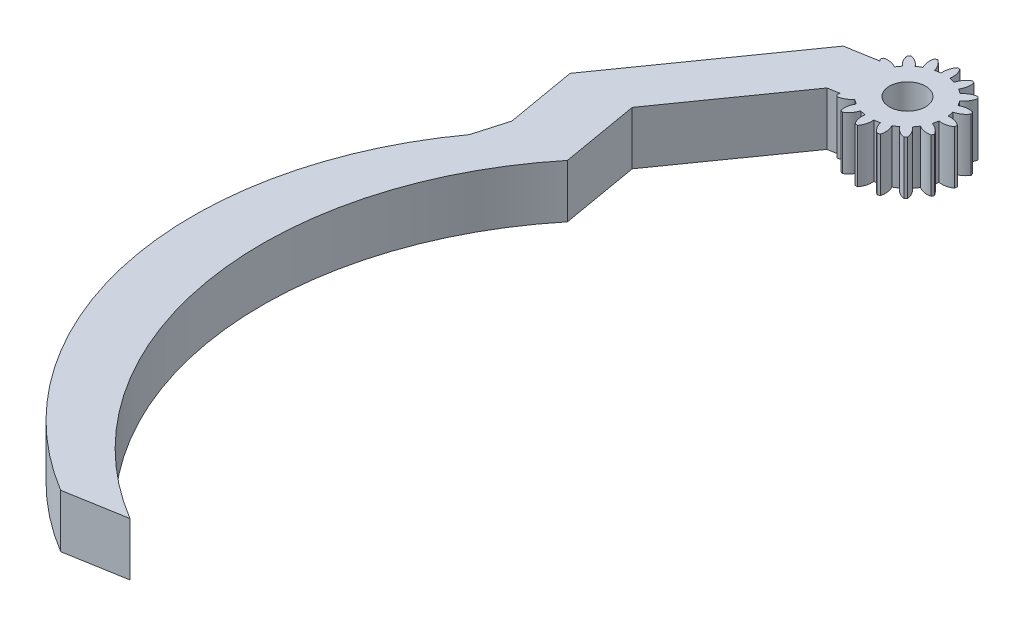
SolidWorks part; units mm, degrees
ref_plane "Front Plane" through (0, 0, 0) normal (0, 0, 1) x (1, 0, 0)
ref_plane "Top Plane" through (0, 0, 0) normal (0, 1, 0) x (1, 0, 0)
ref_plane "Right Plane" through (0, 0, 0) normal (1, 0, 0) x (0, 0, -1)
sketch "Sketch1" plane through (0, 0, 0) normal (0, 1, 0) x (1, 0, 0)
  line L0 (3.0203, 31.1561) -> (1.3998, 30.8763)
  line L1 (1.3998, 30.8763) -> (-10.1283, 14.5359)
  line L2 (-10.1283, 14.5359) -> (-8.192, 3.3226)
  line L3 (4.8849, -72.4068) -> (-3.5689, -73.8666)
  line L4 (-18.4085, -0.4977) -> (-17.0513, 4.211)
  line L5 (-17.0513, 4.211) -> (-18.7961, 14.3151)
  line L6 (-18.7961, 14.3151) -> (-2.6227, 37.2399)
  line L7 (-2.6227, 37.2399) -> (1.8368, 38.01)
  arc A0 (-8.192, 3.3226) -> (4.8849, -72.4068) centre (31.0906, -28.8879) ccw
  arc A1 (-18.4085, -0.4977) -> (-3.5689, -73.8666) centre (22.6783, -30.3727) ccw
  arc A2 (1.6267, 38.3141) -> (1.8368, 38.01) centre (3.8161, 39.6017) ccw
  arc A3 (1.7775, 38.6536) -> (1.6267, 38.3141) centre (8.2284, 35.5846) ccw
  arc A4 (3.6347, 38.3205) -> (1.7775, 38.6536) centre (2.2897, 36.1658) ccw
  arc A5 (4.1104, 38.9948) -> (3.6347, 38.3205) centre (8.2284, 35.5846) ccw
  arc A6 (3.1738, 40.6327) -> (4.1104, 38.9948) centre (5.6893, 40.9845) ccw
  arc A7 (3.443, 40.8886) -> (3.1738, 40.6327) centre (8.2284, 35.5846) ccw
  arc A8 (5.0314, 39.8701) -> (3.443, 40.8886) centre (2.9642, 38.3942) ccw
  arc A9 (5.7289, 40.3111) -> (5.0314, 39.8701) centre (8.2284, 35.5846) ccw
  arc A10 (5.4904, 42.1828) -> (5.7289, 40.3111) centre (7.949, 41.5451) ccw
  arc A11 (5.837, 42.3162) -> (5.4904, 42.1828) centre (8.2284, 35.5846) ccw
  arc A12 (6.9147, 40.7674) -> (5.837, 42.3162) centre (4.4401, 40.1948) ccw
  arc A13 (7.7279, 40.9078) -> (6.9147, 40.7674) centre (8.2284, 35.5846) ccw
  arc A14 (8.2238, 42.7283) -> (7.7279, 40.9078) centre (10.2513, 41.1983) ccw
  arc A15 (8.5951, 42.7189) -> (8.2238, 42.7283) centre (8.2284, 35.5846) ccw
  arc A16 (8.9981, 40.8756) -> (8.5951, 42.7189) centre (6.4927, 41.2936) ccw
  arc A17 (9.8031, 40.6941) -> (8.9981, 40.8756) centre (8.2284, 35.5846) ccw
  arc A18 (10.958, 42.1863) -> (9.8031, 40.6941) centre (12.2456, 39.9969) ccw
  arc A19 (11.2974, 42.0355) -> (10.958, 42.1863) centre (8.2284, 35.5846) ccw
  arc A20 (10.9643, 40.1783) -> (11.2974, 42.0355) centre (8.8096, 41.5233) ccw
  arc A21 (11.6386, 39.7026) -> (10.9643, 40.1783) centre (8.2284, 35.5846) ccw
  arc A22 (13.2766, 40.6392) -> (11.6386, 39.7026) centre (13.6283, 38.1237) ccw
  arc A23 (13.5325, 40.37) -> (13.2766, 40.6392) centre (8.2284, 35.5846) ccw
  arc A24 (12.514, 38.7817) -> (13.5325, 40.37) centre (11.038, 40.8488) ccw
  arc A25 (12.9549, 38.0841) -> (12.514, 38.7817) centre (8.2284, 35.5846) ccw
  arc A26 (14.8266, 38.3226) -> (12.9549, 38.0841) centre (14.1889, 35.864) ccw
  arc A27 (14.96, 37.976) -> (14.8266, 38.3226) centre (8.2284, 35.5846) ccw
  arc A28 (13.4112, 36.8983) -> (14.96, 37.976) centre (12.8387, 39.3729) ccw
  arc A29 (13.5516, 36.0851) -> (13.4112, 36.8983) centre (8.2284, 35.5846) ccw
  arc A30 (15.3722, 35.5892) -> (13.5516, 36.0851) centre (13.8421, 33.5617) ccw
  arc A31 (15.3627, 35.2179) -> (15.3722, 35.5892) centre (8.2284, 35.5846) ccw
  arc A32 (13.5194, 34.8149) -> (15.3627, 35.2179) centre (13.9374, 37.3203) ccw
  arc A33 (13.338, 34.0099) -> (13.5194, 34.8149) centre (8.2284, 35.5846) ccw
  arc A34 (14.8301, 32.855) -> (13.338, 34.0099) centre (12.6407, 31.5674) ccw
  arc A35 (14.6793, 32.5156) -> (14.8301, 32.855) centre (8.2284, 35.5846) ccw
  arc A36 (12.8221, 32.8487) -> (14.6793, 32.5156) centre (14.1671, 35.0034) ccw
  arc A37 (12.3464, 32.1744) -> (12.8221, 32.8487) centre (8.2284, 35.5846) ccw
  arc A38 (13.2831, 30.5365) -> (12.3464, 32.1744) centre (10.7675, 30.1847) ccw
  arc A39 (13.0138, 30.2805) -> (13.2831, 30.5365) centre (8.2284, 35.5846) ccw
  arc A40 (11.4255, 31.299) -> (13.0138, 30.2805) centre (13.4926, 32.775) ccw
  arc A41 (10.7279, 30.8581) -> (11.4255, 31.299) centre (8.2284, 35.5846) ccw
  arc A42 (10.9665, 28.9864) -> (10.7279, 30.8581) centre (8.5078, 29.6241) ccw
  arc A43 (10.6198, 28.853) -> (10.9665, 28.9864) centre (8.2284, 35.5846) ccw
  arc A44 (9.5421, 30.4018) -> (10.6198, 28.853) centre (12.0167, 30.9744) ccw
  arc A45 (8.7289, 30.2614) -> (9.5421, 30.4018) centre (8.2284, 35.5846) ccw
  arc A46 (8.233, 28.4408) -> (8.7289, 30.2614) centre (6.2056, 29.9709) ccw
  arc A47 (7.8617, 28.4503) -> (8.233, 28.4408) centre (8.2284, 35.5846) ccw
  arc A48 (7.4587, 30.2936) -> (7.8617, 28.4503) centre (9.9641, 29.8756) ccw
  arc A49 (6.6537, 30.475) -> (7.4587, 30.2936) centre (8.2284, 35.5846) ccw
  arc A50 (5.4989, 28.9829) -> (6.6537, 30.475) centre (4.2113, 31.1723) ccw
  arc A51 (5.1594, 29.1337) -> (5.4989, 28.9829) centre (8.2284, 35.5846) ccw
  arc A52 (5.4925, 30.9909) -> (5.1594, 29.1337) centre (7.6472, 29.6459) ccw
  arc A53 (4.8182, 31.4666) -> (5.4925, 30.9909) centre (8.2284, 35.5846) ccw
  arc A54 (3.1803, 30.5299) -> (4.8182, 31.4666) centre (2.8286, 33.0455) ccw
  arc A55 (2.9244, 30.7992) -> (3.1803, 30.5299) centre (8.2284, 35.5846) ccw
  arc A56 (3.0203, 31.1561) -> (2.9244, 30.7992) centre (5.4188, 30.3204) ccw
  circle A57 centre (8.2284, 35.5846) radius 2.585
extrude "Boss-Extrude1" add sketch "Sketch1" along normal blind 7.62
